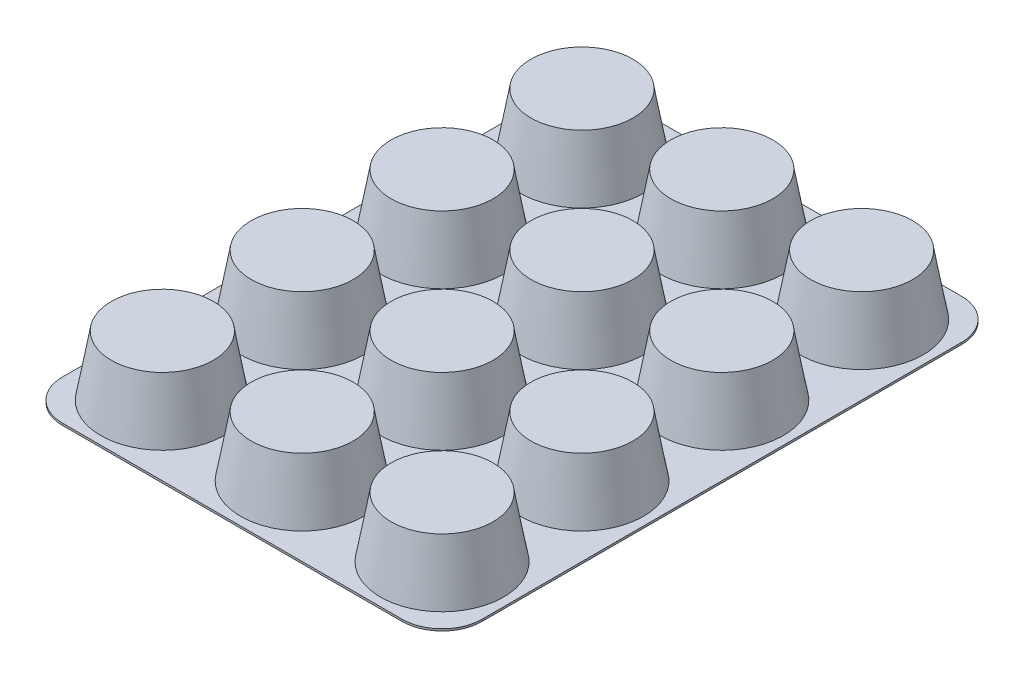
SolidWorks part; units mm, degrees
ref_plane "Front Plane" through (0, 0, 0) normal (0, 0, 1) x (1, 0, 0)
ref_plane "Top Plane" through (0, 0, 0) normal (0, 1, 0) x (1, 0, 0)
ref_plane "Right Plane" through (0, 0, 0) normal (1, 0, 0) x (0, 0, -1)
sketch "Sketch2" plane through (0, 0, 0) normal (0, 1, 0) x (1, 0, 0)
  line L1 (-133.35, -177.8) -> (133.35, -177.8)
  line L2 (-133.35, -177.8) -> (-133.35, 177.8)
  line L3 (-133.35, 177.8) -> (133.35, 177.8)
  line L4 (133.35, -177.8) -> (133.35, 177.8)
  line L5 (-133.35, -177.8) -> (133.35, 177.8) construction
  line L6 (-133.35, 177.8) -> (133.35, -177.8) construction
  point P0 (0, 0)
  dimension "D1" = 355.6
  dimension "D2" = 266.7
extrude "Boss-Extrude1" add sketch "Sketch2" along normal blind 1.27
sketch "Sketch3" plane through (0, 0, 0) normal (0, -1, 0) x (-1, 0, 0)
  line L0 (133.35, 177.8) -> (133.35, -177.8) construction
  line L1 (133.35, -177.8) -> (-133.35, -177.8) construction
  circle A0 centre (88.9, -133.35) radius 39.37
  dimension "D1" = 78.74
  dimension "D2" = 44.45
  dimension "D3" = 44.45
extrude "Boss-Extrude2" add sketch "Sketch3" against normal blind 39.37 draft 10
sketch "Sketch4" plane through (0, 0, 0) normal (0, -1, 0) x (-1, 0, 0)
  line L0 (133.35, 177.8) -> (133.35, -177.8) construction
  line L1 (133.35, -177.8) -> (-133.35, -177.8) construction
  circle A0 centre (88.9, -133.35) radius 38.1
  point P6 (224.3183, -182.0067)
  dimension "D1" = 76.2
  dimension "D2" = 44.45
  dimension "D3" = 44.45
extrude "Cut-Extrude1" cut sketch "Sketch4" against normal blind 38.1 draft 10
pattern_linear "LPattern3" count 3 spacing 88.9 along (1, 0, 0) count 4 spacing 88.9 along (0, 0, -1) of "Cut-Extrude1", "Boss-Extrude2"
fillet "Fillet1" radius 25.4 4 edges at (133.35, 0.635, 177.8) (-133.35, 0.635, 177.8) (-133.35, 0.635, -177.8) (133.35, 0.635, -177.8)
